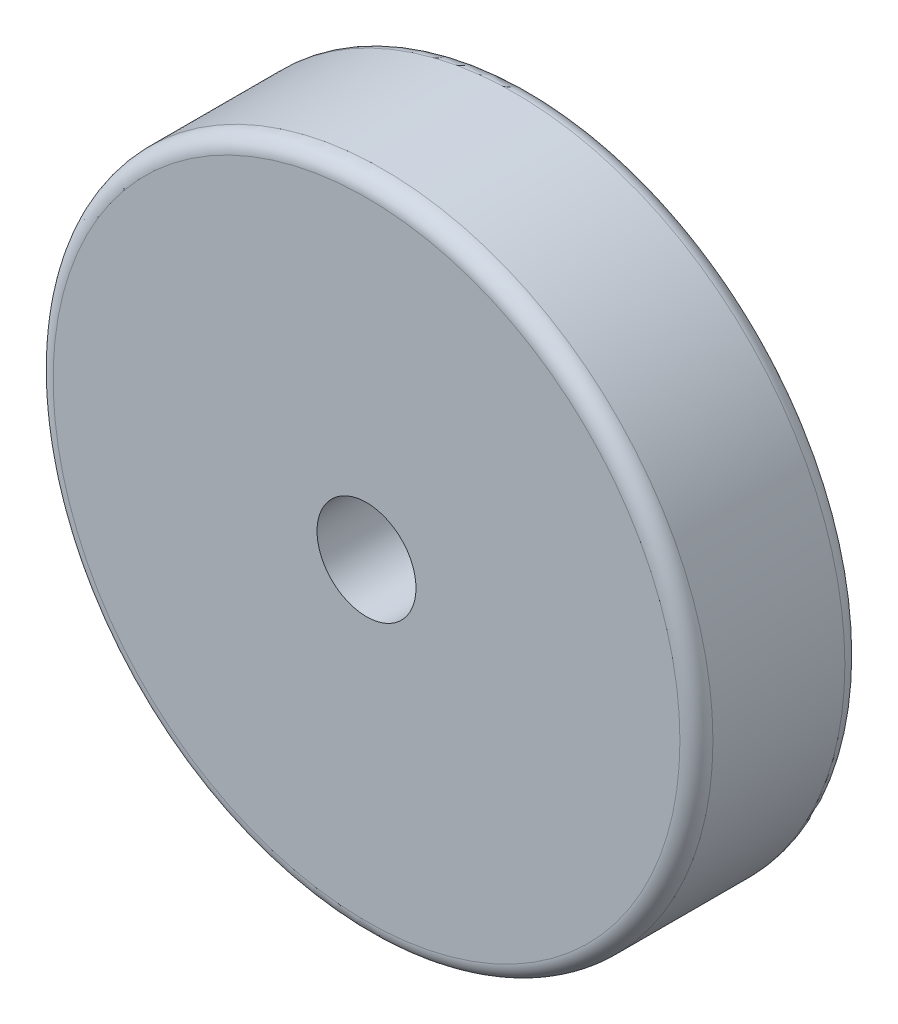
SolidWorks part; units mm, degrees
ref_plane "前视基准面" through (0, 0, 0) normal (0, 0, 1) x (1, 0, 0)
ref_plane "上视基准面" through (0, 0, 0) normal (0, 1, 0) x (1, 0, 0)
ref_plane "右视基准面" through (0, 0, 0) normal (1, 0, 0) x (0, 0, -1)
sketch "草图1" plane through (0, 0, 0) normal (0, 0, 1) x (1, 0, 0)
  circle A0 centre (0, 0) radius 20
  circle A1 centre (0, 0) radius 3
  dimension "D1" = 40
  dimension "D2" = 6
extrude "凸台-拉伸1" add sketch "草图1" along normal blind 10
fillet "圆角1" radius 1 2 edges at (20, 0, 0) (20, 0, 10)
